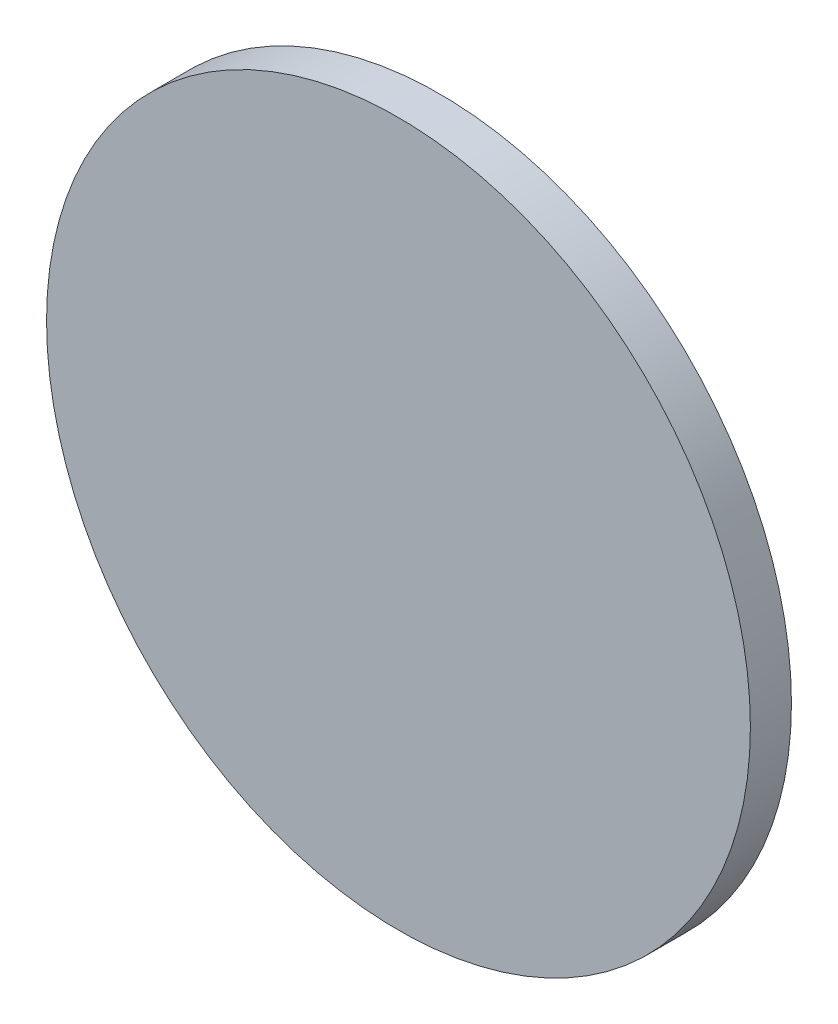
SolidWorks part; units mm, degrees
material "Verre"
ref_plane "Plan de face" through (0, 0, 0) normal (0, 0, 1) x (1, 0, 0)
ref_plane "Plan de dessus" through (0, 0, 0) normal (0, 1, 0) x (1, 0, 0)
ref_plane "Plan de droite" through (0, 0, 0) normal (1, 0, 0) x (0, 0, -1)
sketch "Esquisse1" plane through (0, 0, 0) normal (0, 0, 1) x (1, 0, 0)
  circle A0 centre (0, 0) radius 6
  dimension "D1" = 12
extrude "Boss.-Extru.1" add sketch "Esquisse1" along normal blind 0.7
